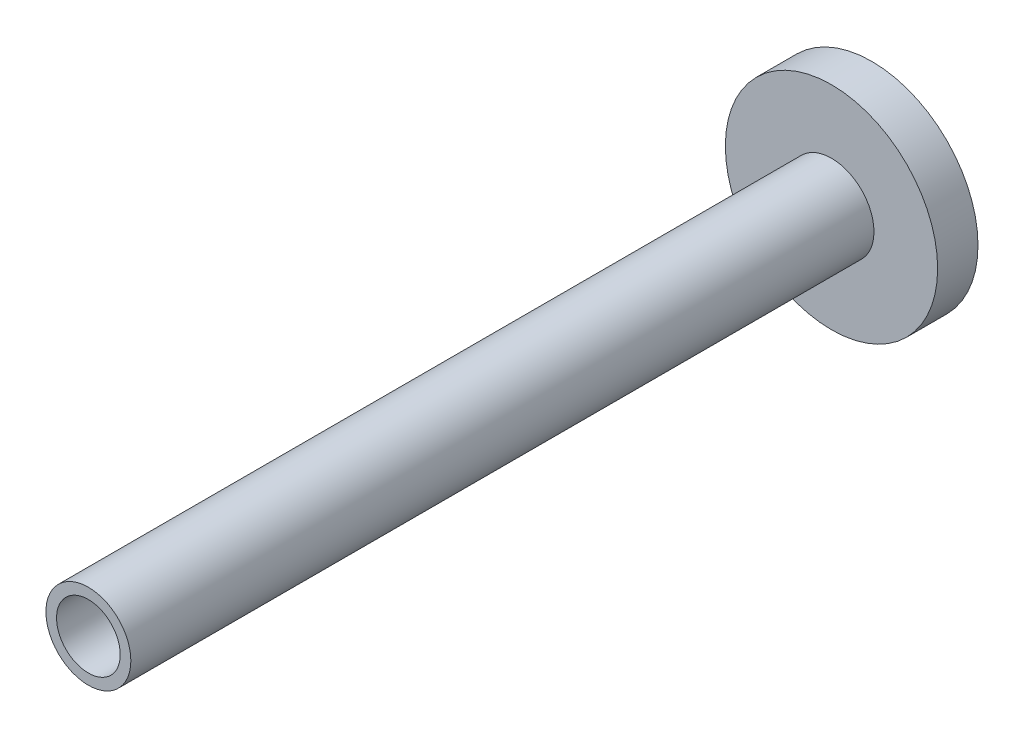
SolidWorks part; units mm, degrees
material "不锈钢 (铁素体)"
ref_plane "前视基准面" through (0, 0, 0) normal (0, 0, 1) x (1, 0, 0)
ref_plane "上视基准面" through (0, 0, 0) normal (0, 1, 0) x (1, 0, 0)
ref_plane "右视基准面" through (0, 0, 0) normal (1, 0, 0) x (0, 0, -1)
sketch "草图1" plane through (0, 0, 0) normal (0, 0, 1) x (1, 0, 0)
  circle A0 centre (0, 0) radius 5
  dimension "D1" = 10
extrude "凸台-拉伸1" add sketch "草图1" along normal blind 1.9
sketch "草图2" plane through (0, 0, 1.9) normal (0, 0, 1) x (1, 0, 0)
  circle A0 centre (0, 0) radius 2
  dimension "D1" = 4
extrude "凸台-拉伸2" add sketch "草图2" along normal blind 35
sketch "草图3" plane through (0, 0, 36.9) normal (0, 0, 1) x (1, 0, 0)
  circle A0 centre (0, 0) radius 1.5
  dimension "D1" = 3
extrude "切除-拉伸1" cut sketch "草图3" against normal blind 12
cosmetic thread "装饰螺纹线1" parameters "D2"=3.6
